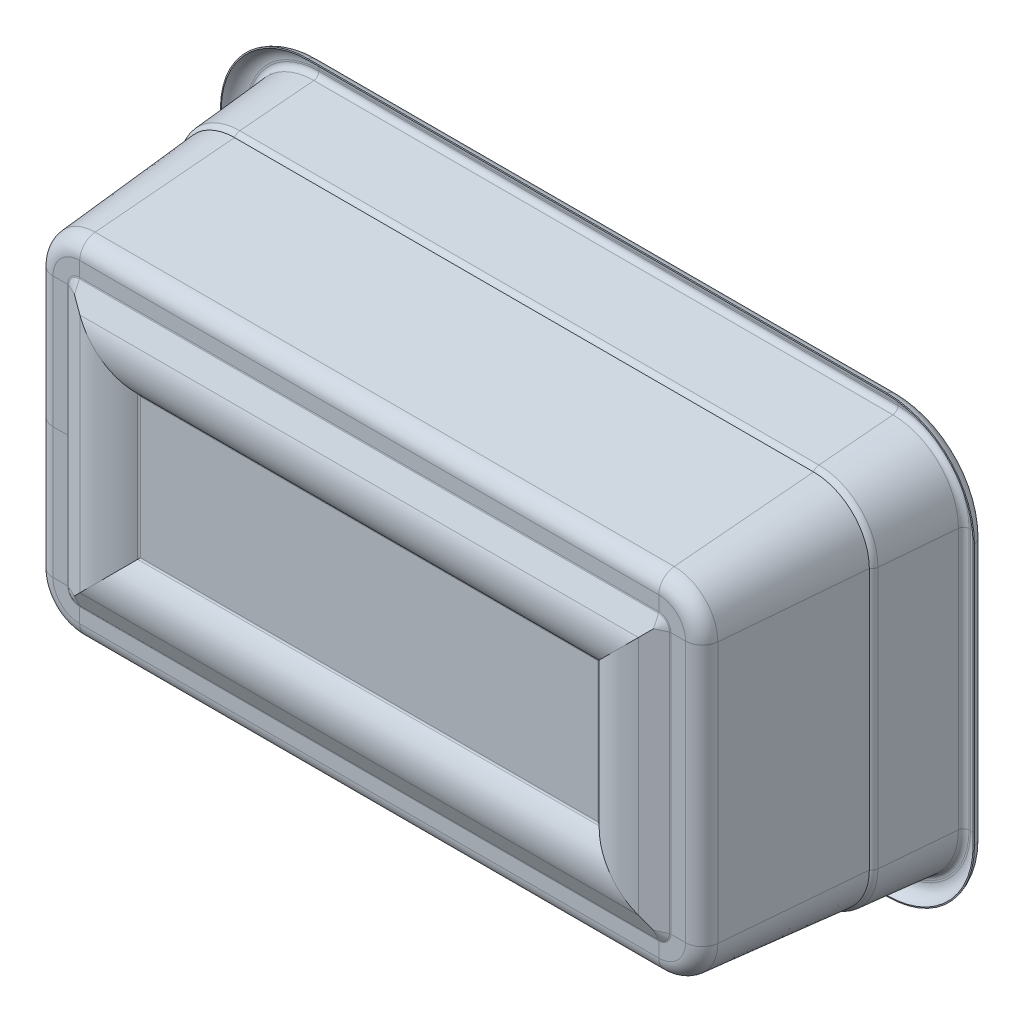
SolidWorks part; units mm, degrees
ref_plane "Front Plane" through (0, 0, 0) normal (0, 0, 1) x (1, 0, 0)
ref_plane "Top Plane" through (0, 0, 0) normal (0, 1, 0) x (1, 0, 0)
ref_plane "Right Plane" through (0, 0, 0) normal (1, 0, 0) x (0, 0, -1)
sketch "Sketch - upper bounding box" plane through (0, 0, 0) normal (0, 0, 1) x (1, 0, 0)
  line L8 (-161.036, -86.36) -> (161.036, -86.36)
  line L9 (-161.036, 86.36) -> (-161.036, -86.36)
  line L10 (161.036, 86.36) -> (-161.036, 86.36)
  line L11 (161.036, -86.36) -> (161.036, 86.36)
  line L16 (-170.18, -95.25) -> (170.18, -95.25)
  line L17 (170.18, -95.25) -> (170.18, 95.25)
  line L18 (170.18, 95.25) -> (-170.18, 95.25)
  line L19 (-170.18, 95.25) -> (-170.18, -95.25)
sketch "Sketch1" plane through (0, 0, 0) normal (0, 0, 1) x (1, 0, 0)
  line L1 (-169.672, -91.567) -> (169.672, -91.567)
  line L2 (-169.672, -91.567) -> (-169.672, 91.567)
  line L3 (-169.672, 91.567) -> (169.672, 91.567)
  line L4 (169.672, -91.567) -> (169.672, 91.567)
  line L5 (-169.672, -91.567) -> (169.672, 91.567) construction
  line L6 (-169.672, 91.567) -> (169.672, -91.567) construction
  line L7 (160.528, -82.677) -> (-160.528, -82.677)
  line L8 (160.528, -82.677) -> (160.528, 82.677)
  line L9 (160.528, 82.677) -> (-160.528, 82.677)
  line L10 (-160.528, -82.677) -> (-160.528, 82.677)
  line L11 (160.528, -82.677) -> (-160.528, 82.677) construction
  line L12 (160.528, 82.677) -> (-160.528, -82.677) construction
  point P0 (0, 0)
  point P6 (0, 0)
  dimension "D1" = 339.344
  dimension "D2" = 183.134
  dimension "D3" = 165.354
  dimension "D4" = 321.056
  dimension "D5" = 8.89
  dimension "D6" = 9.144
ref_plane "Plane1" through (0, 0, 107.95) normal (0, 0, 1) x (1, 0, 0)
sketch "Sketch - lower bounding box" plane through (0, 0, 107.95) normal (0, 0, 1) x (1, 0, 0)
  line L1 (-149.733, -77.978) -> (149.733, -77.978)
  line L2 (-149.733, -77.978) -> (-149.733, 77.978)
  line L3 (-149.733, 77.978) -> (149.733, 77.978)
  line L4 (149.733, -77.978) -> (149.733, 77.978)
  line L5 (-149.733, -77.978) -> (149.733, 77.978) construction
  line L6 (-149.733, 77.978) -> (149.733, -77.978) construction
  point P0 (0, 0)
  dimension "D1" = 155.956
  dimension "D2" = 299.466
sketch "Sketch3" plane through (0, 0, 107.95) normal (0, 0, 1) x (1, 0, 0)
  line L0 (-149.733, -58.928) -> (-149.733, 58.928)
  line L1 (-149.733, -77.978) -> (-149.733, 77.978) construction
  line L2 (-130.683, 77.978) -> (130.683, 77.978)
  line L3 (-149.733, 77.978) -> (149.733, 77.978) construction
  line L4 (149.733, 58.928) -> (149.733, -58.928)
  line L5 (149.733, -77.978) -> (149.733, 77.978) construction
  line L6 (-130.683, -77.978) -> (130.683, -77.978)
  line L7 (-149.733, -77.978) -> (149.733, -77.978) construction
  arc A0 (-149.733, 58.928) -> (-130.683, 77.978) centre (-130.683, 58.928) cw
  arc A1 (-149.733, -58.928) -> (-130.683, -77.978) centre (-130.683, -58.928) ccw
  arc A2 (130.683, 77.978) -> (149.733, 58.928) centre (130.683, 58.928) cw
  arc A3 (130.683, -77.978) -> (149.733, -58.928) centre (130.683, -58.928) ccw
  dimension "D1" = 19.05
sketch "Sketch4" plane through (0, 0, 0) normal (0, 1, 0) x (1, 0, 0)
  line L0 (-147.0495, -114.3) -> (49852.9505, -114.3) construction
  line L1 (-130.683, -107.95) -> (130.683, -107.95) construction
  line L2 (-150.3416, -100.9941) -> (-149.733, -107.95) construction
  line L3 (-149.733, -107.95) -> (-142.7506, -107.95) construction
  line L6 (-150.3416, -100.9941) -> (-155.8441, -38.1)
  line L7 (-103.2269, -107.95) -> (-101.9569, -107.95)
  line L8 (-135.5687, -108.069) -> (-126.0339, -112.5152)
  line L9 (-142.7506, -107.95) -> (-136.1055, -107.95)
  line L10 (-157.3306, -35.6804) -> (-160.2523, -2.286)
  line L11 (0, 0) -> (-50000, 0) construction
  line L12 (-163.4503, 0) -> (-162.747, 0)
  arc A0 (-155.8441, -38.1) -> (-157.3306, -35.6804) centre (-154.1677, -35.4036) cw
  arc A1 (-160.2523, -2.286) -> (-162.747, 0) centre (-162.747, -2.5043) ccw
  arc A2 (-169.672, -5.08) -> (-163.4503, 0) centre (-163.4503, -6.35) cw
  arc A4 (-104.1492, -108.3469) -> (-103.2269, -107.95) centre (-103.2269, -109.22) cw
  arc A5 (-126.0339, -112.5152) -> (-104.1492, -108.3469) centre (-117.983, -95.25) ccw
  arc A6 (-136.1055, -107.95) -> (-135.5687, -108.069) centre (-136.1055, -109.22) cw
  arc A7 (-150.3416, -100.9941) -> (-142.7506, -107.95) centre (-142.7506, -100.33) ccw
  point P0 (-149.733, -107.95)
  point P8 (-117.983, -114.3)
  point P24 (-169.672, 0)
  dimension "D1" = 1.27
  dimension "D2" = 6.35
  dimension "D3" = 7.62
  dimension "D7" = 19.05
  dimension "D12" = 3.175
  dimension "D13" = 6.35
  dimension "D4" = 85
  dimension "D5" = 31.75
  dimension "D6" = 25
  dimension "D8" = 1.27
  dimension "D9" = 76.2
  dimension "D10" = 35.814
  dimension "D11" = 1.27
  dimension "D14" = 5.08
sketch "Sketch12" plane through (0, 0, 0) normal (0, 1, 0) x (1, 0, 0)
  line L2 (-142.7506, -107.95) -> (-136.1055, -107.95) construction
  line L3 (-150.3416, -100.9941) -> (-155.8441, -38.1) construction
  line L4 (-157.3306, -35.6804) -> (-160.2523, -2.286) construction
  line L5 (-163.4503, 0) -> (-162.747, 0) construction
  line L8 (-142.7506, -107.95) -> (-136.1055, -107.95)
  line L9 (-150.3416, -100.9941) -> (-155.8441, -38.1)
  line L10 (-157.3306, -35.6804) -> (-160.2523, -2.286)
  line L11 (-163.4503, 0) -> (-162.747, 0)
  line L12 (-135.5687, -108.069) -> (-135.354, -107.6086)
  line L13 (-163.4503, 0.508) -> (-162.747, 0.508)
  line L14 (-156.8246, -35.6361) -> (-159.7462, -2.2417)
  line L15 (-149.8355, -100.9499) -> (-155.3614, -37.7886)
  line L16 (-142.7506, -107.442) -> (-136.1055, -107.442)
  line L19 (-170.1697, -4.9784) -> (-169.672, -5.08)
  line L22 (-135.5687, -108.069) -> (-126.0339, -112.5152) construction
  line L23 (-135.354, -107.6086) -> (-125.8192, -112.0548) construction
  arc A2 (-135.5687, -108.069) -> (-136.1055, -107.95) centre (-136.1055, -109.22) ccw construction
  arc A3 (-150.3416, -100.9941) -> (-142.7506, -107.95) centre (-142.7506, -100.33) ccw construction
  arc A4 (-157.3306, -35.6804) -> (-155.8441, -38.1) centre (-154.1677, -35.4036) ccw construction
  arc A5 (-160.2523, -2.286) -> (-162.747, 0) centre (-162.747, -2.5043) ccw construction
  arc A6 (-163.4503, 0) -> (-169.672, -5.08) centre (-163.4503, -6.35) ccw construction
  arc A9 (-135.5687, -108.069) -> (-136.1055, -107.95) centre (-136.1055, -109.22) ccw
  arc A10 (-150.3416, -100.9941) -> (-142.7506, -107.95) centre (-142.7506, -100.33) ccw
  arc A11 (-157.3306, -35.6804) -> (-155.8441, -38.1) centre (-154.1677, -35.4036) ccw
  arc A12 (-160.2523, -2.286) -> (-162.747, 0) centre (-162.747, -2.5043) ccw
  arc A13 (-163.4503, 0) -> (-169.672, -5.08) centre (-163.4503, -6.35) ccw
  arc A14 (-163.4503, 0.508) -> (-170.1697, -4.9784) centre (-163.4503, -6.35) ccw
  arc A15 (-159.7462, -2.2417) -> (-162.747, 0.508) centre (-162.747, -2.5043) ccw
  arc A16 (-156.8246, -35.6361) -> (-155.3614, -37.7886) centre (-154.1677, -35.4036) ccw
  arc A17 (-149.8355, -100.9499) -> (-142.7506, -107.442) centre (-142.7506, -100.33) ccw
  arc A18 (-135.354, -107.6086) -> (-136.1055, -107.442) centre (-136.1055, -109.22) ccw
  arc A20 (-126.0339, -112.5152) -> (-117.983, -114.3) centre (-117.983, -95.25) ccw construction
  arc A21 (-125.8192, -112.0548) -> (-117.983, -113.792) centre (-117.983, -95.25) ccw construction
  dimension "D1" = 0.508
sweep "Sweep6" add profiles "Sketch12" path "Sketch3"
sketch "Sketch13" plane through (0, 0, 0) normal (0, 1, 0) x (1, 0, 0)
  line L0 (-103.2269, -107.95) -> (-101.9569, -107.95) construction
  line L1 (-135.5687, -108.069) -> (-126.0339, -112.5152) construction
  line L6 (-103.2269, -107.95) -> (-101.9569, -107.95)
  line L7 (-135.5687, -108.069) -> (-126.0339, -112.5152)
  line L9 (-135.354, -107.6086) -> (-125.8192, -112.0548)
  line L10 (-103.2269, -107.442) -> (-101.9569, -107.442)
  line L11 (-135.5687, -108.069) -> (-135.354, -107.6086)
  line L12 (-101.9569, -107.95) -> (-101.9569, -107.442)
  arc A0 (-103.2269, -107.95) -> (-104.1492, -108.3469) centre (-103.2269, -109.22) ccw construction
  arc A1 (-126.0339, -112.5152) -> (-104.1492, -108.3469) centre (-117.983, -95.25) ccw construction
  arc A7 (-103.2269, -107.95) -> (-104.1492, -108.3469) centre (-103.2269, -109.22) ccw
  arc A8 (-126.0339, -112.5152) -> (-104.1492, -108.3469) centre (-117.983, -95.25) ccw
  arc A9 (-125.8192, -112.0548) -> (-104.5181, -107.9976) centre (-117.983, -95.25) ccw
  arc A14 (-103.2269, -107.442) -> (-104.5181, -107.9976) centre (-103.2269, -109.22) ccw
  dimension "D1" = 0.508
sketch "Sketch14" plane through (0, 0, 107.95) normal (0, 0, 1) x (1, 0, 0)
  line L0 (-139.2161, 67.4611) -> (-130.683, 58.928)
  arc A0 (-130.683, 70.9956) -> (-142.7506, 58.928) centre (-130.683, 58.928) ccw construction
  arc A1 (-130.683, 70.9956) -> (-142.7506, 58.928) centre (-130.683, 58.928) ccw construction
ref_plane "Plane box corner" through (-35.8775, -35.8775, 0) normal (-0.7071, -0.7071, 0) x (0.7071, -0.7071, 0)
extrude "Boss-Extrude2" add sketch "Sketch13" along normal up to surface (31.4719 mm away) separate body up to plane "Plane box corner"
mirror "Mirror1" about plane through (-103.2269, 0, 109.22) normal (0, 1, 0) of "Boss-Extrude2"
sketch "Sketch15" plane through (0, 0, 0) normal (1, 0, 0) x (0, 0, -1)
  line L7 (-112.0548, 54.0642) -> (-107.6086, 63.599)
  line L9 (-107.6086, 63.599) -> (-108.069, 63.8137)
  line L10 (-108.069, 63.8137) -> (-112.5152, 54.2789)
  line L11 (-107.95, 31.4719) -> (-107.95, 30.2019)
  line L12 (-107.95, 30.2019) -> (-107.442, 30.2019)
  line L13 (-107.442, 30.2019) -> (-107.442, 31.4719)
  line L14 (-112.0548, 54.0642) -> (-107.6086, 63.599)
  line L16 (-107.6086, 63.599) -> (-108.069, 63.8137)
  line L17 (-108.069, 63.8137) -> (-112.5152, 54.2789)
  line L18 (-107.95, 31.4719) -> (-107.95, 30.2019)
  line L19 (-107.95, 30.2019) -> (-107.442, 30.2019)
  line L20 (-107.442, 30.2019) -> (-107.442, 31.4719)
  arc A4 (-112.5152, 54.2789) -> (-108.3469, 32.3942) centre (-95.25, 46.228) ccw
  arc A5 (-107.95, 31.4719) -> (-108.3469, 32.3942) centre (-109.22, 31.4719) ccw
  arc A6 (-107.442, 31.4719) -> (-107.9976, 32.7631) centre (-109.22, 31.4719) ccw
  arc A7 (-112.0548, 54.0642) -> (-107.9976, 32.7631) centre (-95.25, 46.228) ccw
  arc A8 (-112.5152, 54.2789) -> (-108.3469, 32.3942) centre (-95.25, 46.228) ccw
  arc A9 (-107.95, 31.4719) -> (-108.3469, 32.3942) centre (-109.22, 31.4719) ccw
  arc A10 (-107.442, 31.4719) -> (-107.9976, 32.7631) centre (-109.22, 31.4719) ccw
  arc A11 (-112.0548, 54.0642) -> (-107.9976, 32.7631) centre (-95.25, 46.228) ccw
  dimension "D1" = 0
extrude "Boss-Extrude3" add sketch "Sketch15" against normal up to surface (125.8192 mm away) separate body up to plane "Plane box corner"
mirror "Mirror5" about plane through (0, 46.228, 95.25) normal (1, 0, 0) of "Boss-Extrude3"
mirror "Mirror8" about plane through (0, 0, 0) normal (1, 0, 0) of bodies 105
mirror "Mirror9" about plane through (0, 0, 0) normal (0, 1, 0) of bodies 108
combine bodies "Combine1" operation type add bodies to combine 105 108 111 110
sketch "Sketch16" plane through (0, 0, 107.95) normal (0, 0, 1) x (1, 0, 0)
  line L4 (-101.9569, 30.2019) -> (-101.9569, -30.2019)
  line L5 (101.9569, 30.2019) -> (-101.9569, 30.2019)
  line L6 (101.9569, -30.2019) -> (101.9569, 30.2019)
  line L7 (-101.9569, -30.2019) -> (101.9569, -30.2019)
  line L8 (-101.9569, 30.2019) -> (-101.9569, -30.2019)
  line L9 (101.9569, 30.2019) -> (-101.9569, 30.2019)
  line L10 (101.9569, -30.2019) -> (101.9569, 30.2019)
  line L11 (-101.9569, -30.2019) -> (101.9569, -30.2019)
  line M5 (-101.9569, -30.2019) -> (-101.9569, 30.2019)
  line M6 (-101.9569, 30.2019) -> (101.9569, 30.2019)
  line M7 (101.9569, 30.2019) -> (101.9569, -30.2019)
  line M8 (101.9569, -30.2019) -> (-101.9569, -30.2019)
  dimension "D1" = 0
extrude "Boss-Extrude5" add sketch "Sketch16" against normal blind 0.508 contours M5 M8 M7 M6
sketch "Sketch17" plane through (0, 0, 0) normal (0, 0, 1) x (1, 0, 0)
  line L0 (-135.5687, -58.928) -> (-135.5687, -63.8137)
  line L1 (-135.5687, -63.8137) -> (-130.683, -63.8137)
  line L2 (-135.5687, -58.928) -> (-130.683, -58.928)
  line L3 (-130.683, -58.928) -> (-130.683, -63.8137)
  arc A0 (-135.5687, -58.928) -> (-130.683, -63.8137) centre (-130.683, -58.928) ccw construction
  arc A1 (-135.5687, -58.928) -> (-130.683, -63.8137) centre (-130.683, -58.928) ccw construction
extrude "Cut-Extrude1" cut sketch "Sketch17" along normal through all
sketch "Sketch18" plane through (0, -58.928, 0) normal (0, -1, 0) x (1, 0, 0)
  line L4 (-130.683, 110.3472) -> (-135.5687, 108.069)
  line L6 (-130.683, 110.3472) -> (-135.5687, 108.069)
  line L7 (-130.683, 109.7867) -> (-130.683, 110.3472)
  line L11 (-130.683, 109.7867) -> (-130.683, 110.3472)
  line L13 (-135.5687, 108.069) -> (-135.354, 107.6086)
  line L15 (-135.5687, 108.069) -> (-135.354, 107.6086)
  line L16 (-135.354, 107.6086) -> (-130.683, 109.7867)
  line L17 (-135.354, 107.6086) -> (-130.683, 109.7867)
  dimension "D1" = 0
revolve "Revolve1" add sketch "Sketch18" angle 90 about L11
mirror "Mirror10" about plane through (0, 0, 0) normal (0, 1, 0) of "Revolve1", "Cut-Extrude1"
mirror "Mirror11" about plane through (0, 0, 0) normal (1, 0, 0) of "Revolve1", "Cut-Extrude1", "Mirror10"
combine bodies "Combine2" operation type add bodies to combine 103 117
